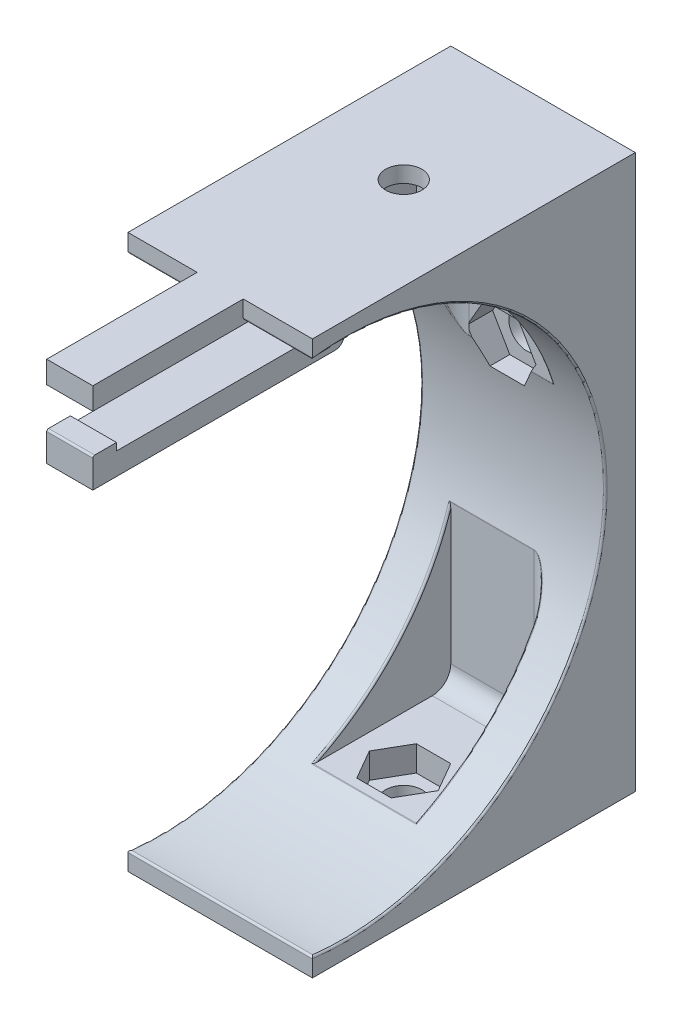
SolidWorks part; units mm, degrees
ref_plane "Front" through (0, 0, 0) normal (0, 0, 1) x (1, 0, 0)
ref_plane "Top" through (0, 0, 0) normal (0, 1, 0) x (1, 0, 0)
ref_plane "Right" through (0, 0, 0) normal (1, 0, 0) x (0, 0, -1)
sketch "Sketch1" plane through (0, 0, 0) normal (0, 0, 1) x (1, 0, 0)
  line L1 (-12.7, 38.1) -> (12.7, 38.1)
  line L2 (-12.7, 38.1) -> (-12.7, -38.1)
  line L3 (-12.7, -38.1) -> (12.7, -38.1)
  line L4 (12.7, 38.1) -> (12.7, -38.1)
  line L5 (-12.7, 38.1) -> (12.7, -38.1) construction
  line L6 (-12.7, -38.1) -> (12.7, 38.1) construction
  point P0 (0, 0)
  dimension "D1" = 25.4
  dimension "D2" = 76.2
extrude "Boss-Extrude1" add sketch "Sketch1" along normal blind 44.45
shell "Shell1" thickness 5.715
sketch "Sketch2" plane through (12.7, 0, 0) normal (1, 0, 0) x (0, 0, -1)
  line L0 (-36.4137, 38.1) -> (-36.4137, -38.1) construction
  line L1 (-44.45, 38.1) -> (0, 38.1) construction
  line L2 (-44.45, -38.1) -> (0, -38.1) construction
  line L7 (0, -38.1) -> (0, 38.1)
  line L8 (0, 38.1) -> (-44.45, 38.1)
  line L9 (-44.45, 38.1) -> (-44.45, -38.1)
  line L10 (-44.45, -38.1) -> (0, -38.1)
  line L11 (0, -38.1) -> (0, 38.1)
  line L12 (0, 38.1) -> (-44.45, 38.1)
  line L13 (-44.45, 38.1) -> (-44.45, -38.1)
  line L14 (-44.45, -38.1) -> (0, -38.1)
  arc A0 (-44.45, 35.56) -> (-44.45, -35.56) centre (-39.9694, 0) cw
  dimension "D2" = 2.54
  dimension "D3" = 2.54
  dimension "D1" = 0
extrude "Cut-Extrude3" cut sketch "Sketch2" against normal through all both contours A0 L0 | L0 A0 L13
sketch "Sketch4" plane through (0, 38.1, 0) normal (0, 1, 0) x (1, 0, 0)
  line L0 (0, -24.4475) -> (0, 24.4475) construction
  line L1 (-13.97, 0) -> (13.97, 0) construction
  circle A0 centre (0, -19.177) radius 2.5
  dimension "D1" = 5
  dimension "D2" = 19.177
extrude "Cut-Extrude4" cut sketch "Sketch4" against normal through all both
sketch "Sketch5" plane through (0, 0, 5.715) normal (0, 0, 1) x (1, 0, 0)
  line L0 (0, -24.4475) -> (0, 24.4475) construction
  line L1 (12.7, 38.1) -> (-12.7, 38.1) construction
  circle A0 centre (0, 11.684) radius 2.5
  dimension "D1" = 5
  dimension "D2" = 26.416
extrude "Cut-Extrude5" cut sketch "Sketch5" against normal through all both
fillet "Fillet1" radius 2.54 2 edges at (0, 32.385, 5.715) (0, -32.385, 5.715)
fillet "Fillet2" radius 0.254 16 edges at (0, 35.56, 44.45) (0, -35.56, 44.45) (-12.7, 0, 4.1282) (12.7, 0, 4.1282) (6.985, -25.8681, 15.1615) (5.0613, -10.7899, 5.7909) (6.985, 23.4535, 12.8673) (0, 32.385, 24.6136) (-6.985, 25.8681, 15.1615) (-5.0613, 10.7899, 5.7909) (-6.985, -23.4535, 12.8673) (0, -32.385, 24.6136) (-3.3356, 10.5464, 5.715) (4.6056, 10.5464, 5.715) (-1.27, -10.5464, 5.715) (-0.2184, 9.1936, 5.3274)
sketch "Sketch6" plane through (0, 32.385, 0) normal (0, -1, 0) x (1, 0, 0)
  circle A0 centre (0, 19.177) radius 2.5 construction
  circle A1 centre (0, 19.177) radius 2.5
sketch "Sketch7" plane through (0, -32.385, 0) normal (0, 1, 0) x (1, 0, 0)
  line L1 (-2.3671, -23.277) -> (2.3671, -23.277)
  line L2 (2.3671, -23.277) -> (4.7343, -19.177)
  line L3 (4.7343, -19.177) -> (2.3671, -15.077)
  line L4 (2.3671, -15.077) -> (-2.3671, -15.077)
  line L5 (-2.3671, -15.077) -> (-4.7343, -19.177)
  line L6 (-4.7343, -19.177) -> (-2.3671, -23.277)
  circle A0 centre (0, -19.177) radius 2.5 construction
  circle A1 centre (0, -19.177) radius 2.5
  circle A2 centre (0, -19.177) radius 4.1 construction
  dimension "D1" = 8.2
extrude "Cut-Extrude6" cut sketch "Sketch7" against normal blind 3.5
sketch "Sketch8" plane through (0, 0, 5.715) normal (0, 0, 1) x (1, 0, 0)
  line L1 (4.7343, 11.684) -> (2.3671, 15.784)
  line L2 (2.3671, 15.784) -> (-2.3671, 15.784)
  line L3 (-2.3671, 15.784) -> (-4.7343, 11.684)
  line L4 (-4.7343, 11.684) -> (-2.3671, 7.584)
  line L5 (-2.3671, 7.584) -> (2.3671, 7.584)
  line L6 (2.3671, 7.584) -> (4.7343, 11.684)
  circle A0 centre (0, 11.684) radius 2.5 construction
  circle A1 centre (0, 11.684) radius 2.5
  circle A2 centre (0, 11.684) radius 4.1 construction
  dimension "D1" = 8.2
extrude "Cut-Extrude7" cut sketch "Sketch8" against normal blind 3.5
sketch "Sketch9" plane through (0, 32.385, 0) normal (0, -1, 0) x (1, 0, 0)
  line L1 (2.3671, 15.077) -> (4.7343, 19.177)
  line L2 (4.7343, 19.177) -> (2.3671, 23.277)
  line L3 (2.3671, 23.277) -> (-2.3671, 23.277)
  line L4 (-2.3671, 23.277) -> (-4.7343, 19.177)
  line L5 (-4.7343, 19.177) -> (-2.3671, 15.077)
  line L6 (-2.3671, 15.077) -> (2.3671, 15.077)
  circle A0 centre (0, 19.177) radius 2.5 construction
  circle A1 centre (0, 19.177) radius 2.5
  circle A2 centre (0, 19.177) radius 4.1 construction
  dimension "D1" = 8.2
extrude "Cut-Extrude8" cut sketch "Sketch9" against normal blind 3.5
sketch "Sketch10" plane through (0, 0, 0) normal (1, 0, 0) x (0, 0, -1)
  line L1 (-30.5295, 38.1) -> (-65.1574, 38.1)
  line L2 (-30.5295, 38.1) -> (-30.5295, 35.052)
  line L3 (-30.5295, 35.052) -> (-65.1574, 35.052)
  line L4 (-65.1574, 38.1) -> (-65.1574, 35.052)
  line L5 (-44.45, -35.8469) -> (-44.45, -38.1)
  line L6 (-44.45, -38.1) -> (0, -38.1)
  line L7 (0, -38.1) -> (0, 38.1)
  line L8 (0, 38.1) -> (-44.45, 38.1)
  line L9 (-44.45, 38.1) -> (-44.45, 35.8469)
  line L10 (-44.45, -35.8469) -> (-44.45, -38.1)
  line L11 (-44.45, -38.1) -> (0, -38.1)
  line L12 (0, -38.1) -> (0, 38.1)
  line L13 (0, 38.1) -> (-44.45, 38.1)
  line L14 (-44.45, 38.1) -> (-44.45, 35.8469)
  line L15 (-30.5295, 35.052) -> (-33.0695, 35.052)
  line L16 (-30.5295, 35.052) -> (-30.5295, 28.702)
  line L17 (-30.5295, 28.702) -> (-33.0695, 28.702)
  line L18 (-33.0695, 35.052) -> (-33.0695, 28.702)
  line L19 (-30.5295, 28.702) -> (-65.1574, 28.702)
  line L20 (-30.5295, 28.702) -> (-30.5295, 26.924)
  line L21 (-31.7995, 25.654) -> (-65.1574, 25.654)
  line L22 (-65.1574, 28.702) -> (-65.1574, 25.654)
  line L23 (-65.1574, 28.702) -> (-61.9009, 28.702)
  line L24 (-65.1574, 28.702) -> (-65.1574, 29.464)
  line L25 (-64.9034, 29.718) -> (-61.9009, 29.718)
  line L26 (-61.9009, 28.702) -> (-61.9009, 29.718)
  arc A0 (-64.9034, 29.718) -> (-65.1574, 29.464) centre (-64.9034, 29.464) ccw
  arc A1 (-30.5295, 26.924) -> (-31.7995, 25.654) centre (-31.7995, 26.924) cw
  arc A3 (-44.4481, -35.8162) -> (-44.4481, 35.8162) centre (-39.9694, 0) ccw
  arc A4 (-44.4481, -35.8162) -> (-44.45, -35.8469) centre (-44.196, -35.8469) ccw
  arc A5 (-44.45, 35.8469) -> (-44.4481, 35.8162) centre (-44.196, 35.8469) ccw
  arc A6 (-44.4481, -35.8162) -> (-44.4481, 35.8162) centre (-39.9694, 0) ccw
  arc A7 (-44.4481, -35.8162) -> (-44.45, -35.8469) centre (-44.196, -35.8469) ccw
  arc A8 (-44.45, 35.8469) -> (-44.4481, 35.8162) centre (-44.196, 35.8469) ccw
  point P26 (-65.1574, 29.718)
  dimension "D6" = 0.254
  dimension "D8" = 1.27
  dimension "D2" = 3.048
  dimension "D3" = 3.048
  dimension "D4" = 1.016
  dimension "D5" = 6.35
  dimension "D7" = 2.54
  dimension "D1" = 0
extrude "Boss-Extrude2" add sketch "Sketch10" along normal mid plane 6.35 contours L2 L1 L4 L3 | L16 L15 L18 L17 | L20 A1 L21 L22 L19 | L24 A0 L25 L26 L23
